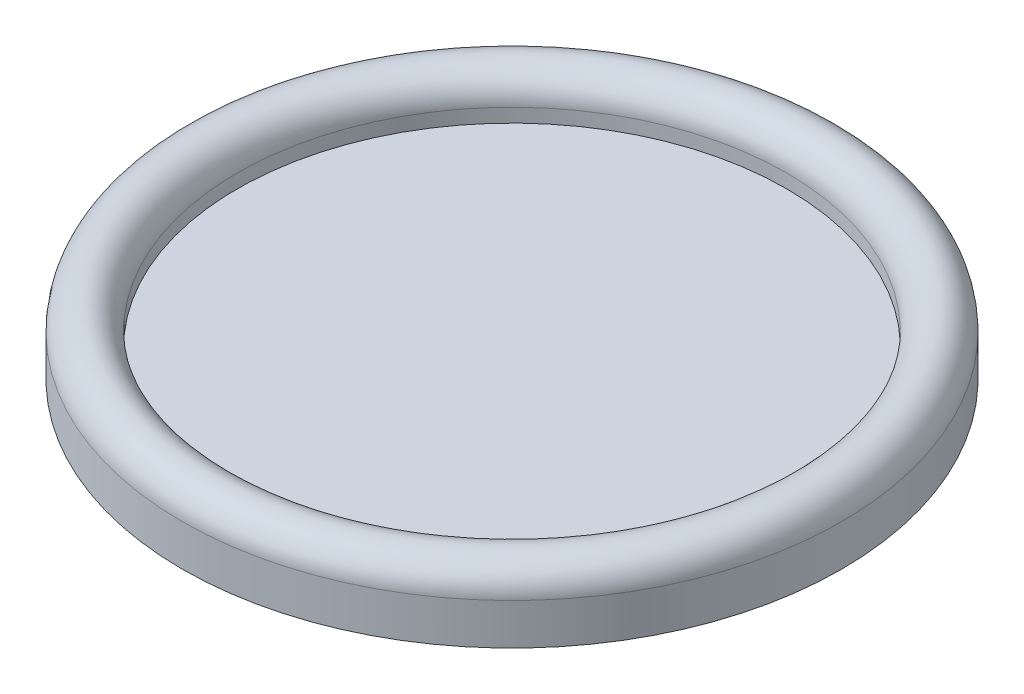
SolidWorks part; units mm, degrees
ref_plane "Front Plane" through (0, 0, 0) normal (0, 0, 1) x (1, 0, 0)
ref_plane "Top Plane" through (0, 0, 0) normal (0, 1, 0) x (1, 0, 0)
ref_plane "Right Plane" through (0, 0, 0) normal (1, 0, 0) x (0, 0, -1)
sketch "Sketch1" plane through (0, 0, 0) normal (0, 0, 1) x (1, 0, 0)
  line L0 (0, 0) -> (-76.2, 0)
  line L1 (-76.2, 0) -> (-76.2, 9.525)
  line L2 (-63.5, 9.525) -> (-63.5, 6.35)
  line L3 (-63.5, 6.35) -> (0, 6.35)
  line L4 (0, 6.35) -> (0, 0)
  line L5 (0, 0) -> (0, -13.5772)
  line L6 (0, -13.5772) -> (5.0763, -13.5772)
  arc A0 (-76.2, 9.525) -> (-63.5, 9.525) centre (-69.85, 9.525) cw
  arc A1 (0, -13.5772) -> (-76.2, 0) centre (0, 207.0416) cw
  point P11 (5.0763, -13.5772)
  point P12 (0, 0)
  dimension "D1" = 6.35
  dimension "D2" = 3.175
  dimension "D3" = 12.7
  dimension "D4" = 76.2
  dimension "D5" = 13.5772
revolve "Revolve2" add sketch "Sketch1" angle 360 about L4
sketch "Sketch2" plane through (0, 6.35, 0) normal (0, 1, 0) x (1, 0, 0)
  circle A0 centre (0, 0) radius 8.5475
